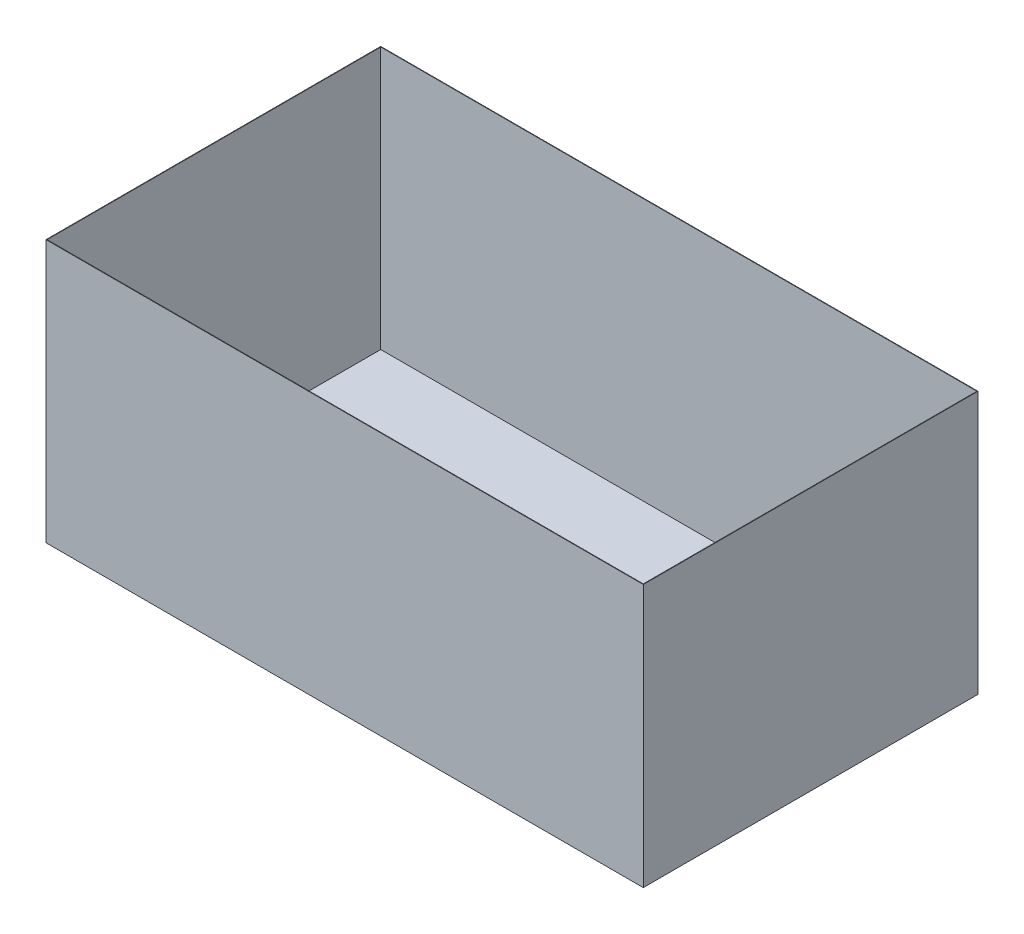
SolidWorks part; units mm, degrees
ref_plane "Front Plane" through (0, 0, 0) normal (0, 0, 1) x (1, 0, 0)
ref_plane "Top Plane" through (0, 0, 0) normal (0, 1, 0) x (1, 0, 0)
ref_plane "Right Plane" through (0, 0, 0) normal (1, 0, 0) x (0, 0, -1)
sketch "Sketch1" plane through (0, 0, 0) normal (1, 0, 0) x (0, 0, -1)
  line L1 (0, 0) -> (1295.4, 0)
  line L2 (0, 0) -> (0, 1016)
  line L3 (0, 1016) -> (1295.4, 1016)
  line L4 (1295.4, 0) -> (1295.4, 1016)
  dimension "D1" = 1295.4
  dimension "D2" = 1016
extrude "Boss-Extrude1" add sketch "Sketch1" against normal blind 2311.4
sketch "Sketch2" plane through (0, 1016, 0) normal (0, 1, 0) x (1, 0, 0)
  line L0 (-2311.4, 1295.4) -> (0, 1295.4) construction
  line L1 (-2, 2) -> (-2309.4, 2)
  line L2 (-2, 2) -> (-2, 1293.4)
  line L3 (-2, 1293.4) -> (-2309.4, 1293.4)
  line L4 (-2309.4, 2) -> (-2309.4, 1293.4)
  line L5 (-2, 2) -> (-2309.4, 1293.4) construction
  line L6 (-2, 1293.4) -> (-2309.4, 2) construction
  line L7 (0, 1295.4) -> (0, 0) construction
  line L8 (-2311.4, 0) -> (0, 0) construction
  line L9 (-2311.4, 1295.4) -> (-2311.4, 0) construction
  point P0 (-1155.7, 647.7)
  dimension "D1" = 2
  dimension "D2" = 2
  dimension "D3" = 2
  dimension "D4" = 2
extrude "Cut-Extrude1" cut sketch "Sketch2" against normal blind 1014
scale "Scale1" scale about centroid uniform scaling yes scale factor 2.54
